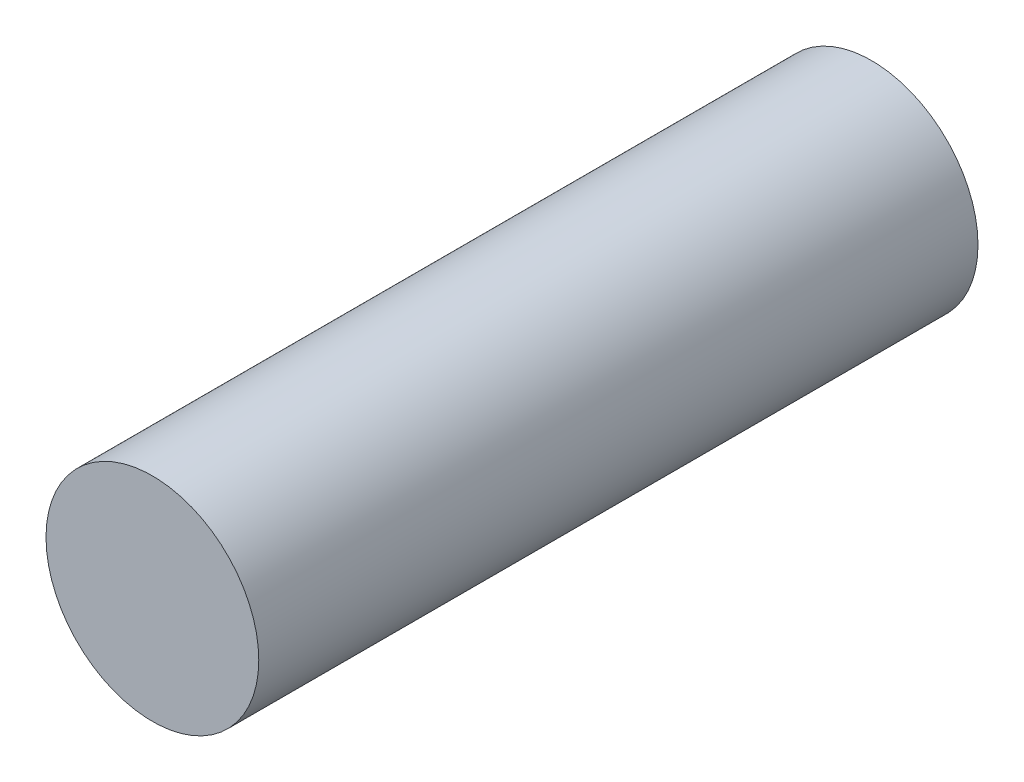
SolidWorks part; units mm, degrees
ref_plane "Front Plane" through (0, 0, 0) normal (0, 0, 1) x (1, 0, 0)
ref_plane "Top Plane" through (0, 0, 0) normal (0, 1, 0) x (1, 0, 0)
ref_plane "Right Plane" through (0, 0, 0) normal (1, 0, 0) x (0, 0, -1)
sketch "Sketch1" plane through (0, 0, 0) normal (0, 0, 1) x (1, 0, 0)
  circle A0 centre (0, 0) radius 7.1
  dimension "D1" = 14.2
extrude "Boss-Extrude1" add sketch "Sketch1" along normal blind 48 contours A0
sketch "Sketch2" plane through (0, 0, 0) normal (0, 0, -1) x (-1, 0, 0)
  circle A0 centre (0, 0) radius 2.5
  dimension "D1" = 5
extrude "Boss-Extrude2" add sketch "Sketch2" along normal blind 2
